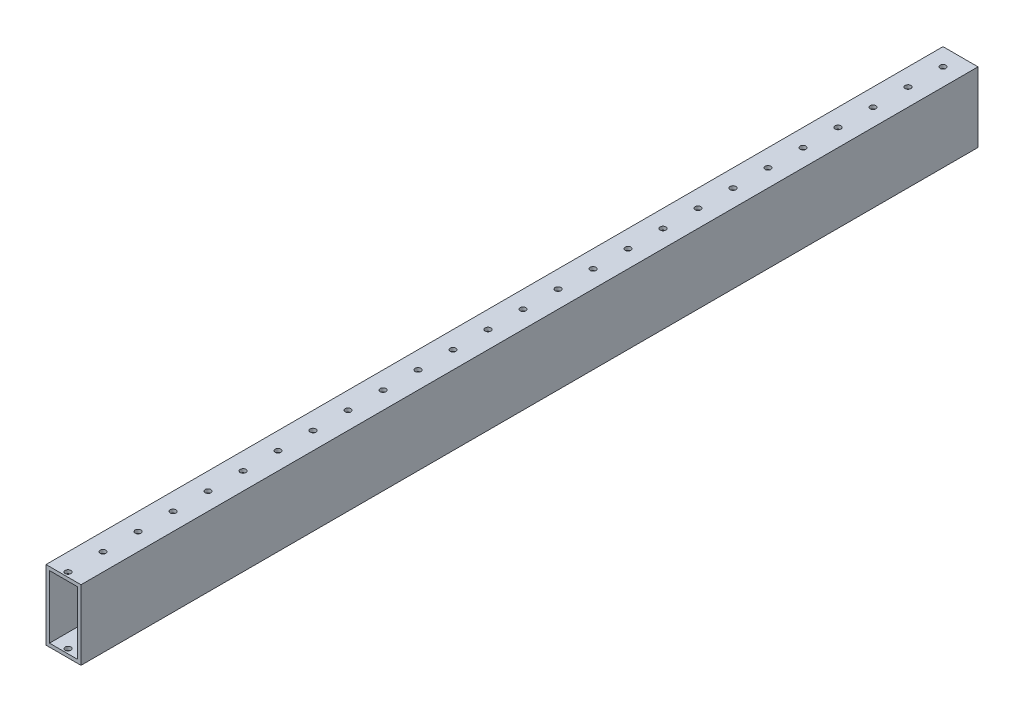
SolidWorks part; units mm, degrees
ref_plane "Alzado" through (0, 0, 0) normal (0, 0, 1) x (1, 0, 0)
ref_plane "Planta" through (0, 0, 0) normal (0, 1, 0) x (1, 0, 0)
ref_plane "Vista lateral" through (0, 0, 0) normal (1, 0, 0) x (0, 0, -1)
sketch "Croquis1" plane through (0, 0, 0) normal (0, 0, 1) x (1, 0, 0)
  line L1 (-12.7, 25.35) -> (12.7, 25.35)
  line L2 (-12.7, 25.35) -> (-12.7, -25.35)
  line L3 (-12.7, -25.35) -> (12.7, -25.35)
  line L4 (12.7, 25.35) -> (12.7, -25.35)
  line L5 (-12.7, 25.35) -> (12.7, -25.35) construction
  line L6 (-12.7, -25.35) -> (12.7, 25.35) construction
  line L7 (-10.16, 22.81) -> (10.16, 22.81)
  line L8 (-10.16, 22.81) -> (-10.16, -22.81)
  line L9 (-10.16, -22.81) -> (10.16, -22.81)
  line L10 (10.16, 22.81) -> (10.16, -22.81)
  line L11 (-10.16, 22.81) -> (10.16, -22.81) construction
  line L12 (-10.16, -22.81) -> (10.16, 22.81) construction
  point P0 (0, 0)
  point P6 (0, 0)
  dimension "D1" = 25.4
  dimension "D2" = 50.7
  dimension "D3" = 2.54
  dimension "D4" = 2.54
extrude "Saliente-Extruir1" add sketch "Croquis1" along normal blind 651
sketch "Croquis2" plane through (0, 25.35, 0) normal (0, 1, 0) x (1, 0, 0)
  line L0 (-12.7, 0) -> (12.7, 0)
  line L1 (12.7, 0) -> (0, 0)
  line L2 (0, -651) -> (0, 0)
  line L3 (12.7, -651) -> (-12.7, -651) construction
  line L4 (0, -12.7) -> (0, -38.1) construction
  circle A0 centre (0, -12.7) radius 2.07
  circle A1 centre (0, -38.1) radius 2.07
  circle A2 centre (0, -38.1) radius 2.07
  circle A3 centre (0, -63.5) radius 2.07
  circle A4 centre (0, -88.9) radius 2.07
  circle A5 centre (0, -114.3) radius 2.07
  circle A6 centre (0, -139.7) radius 2.07
  circle A7 centre (0, -165.1) radius 2.07
  circle A8 centre (0, -190.5) radius 2.07
  circle A9 centre (0, -215.9) radius 2.07
  circle A10 centre (0, -241.3) radius 2.07
  circle A11 centre (0, -266.7) radius 2.07
  circle A12 centre (0, -292.1) radius 2.07
  circle A13 centre (0, -317.5) radius 2.07
  circle A14 centre (0, -342.9) radius 2.07
  circle A15 centre (0, -368.3) radius 2.07
  circle A16 centre (0, -393.7) radius 2.07
  circle A17 centre (0, -419.1) radius 2.07
  circle A18 centre (0, -444.5) radius 2.07
  circle A19 centre (0, -469.9) radius 2.07
  circle A20 centre (0, -495.3) radius 2.07
  circle A21 centre (0, -520.7) radius 2.07
  circle A22 centre (0, -546.1) radius 2.07
  circle A23 centre (0, -571.5) radius 2.07
  circle A24 centre (0, -596.9) radius 2.07
  circle A25 centre (0, -622.3) radius 2.07
  circle A26 centre (0, -647.7) radius 2.07
  dimension "D1" = 4.14
  dimension "D2" = 12.7
  dimension "D3" = 4.14
  dimension "D4" = 25.4
  dimension "D5" = 26
  dimension "D6" = 25.4
extrude "Cortar-Extruir2" cut sketch "Croquis2" against normal blind 54 contours A1 | A0 | A10 | A9 | A8 | A7 | A6 | A5 | A4 | A3 | A18 | A17 | A16 | A15 | A14 | A13 | A12 | A11 | A26 | A25 | A24 | A23 | A22 | A21 | A20 | A19
